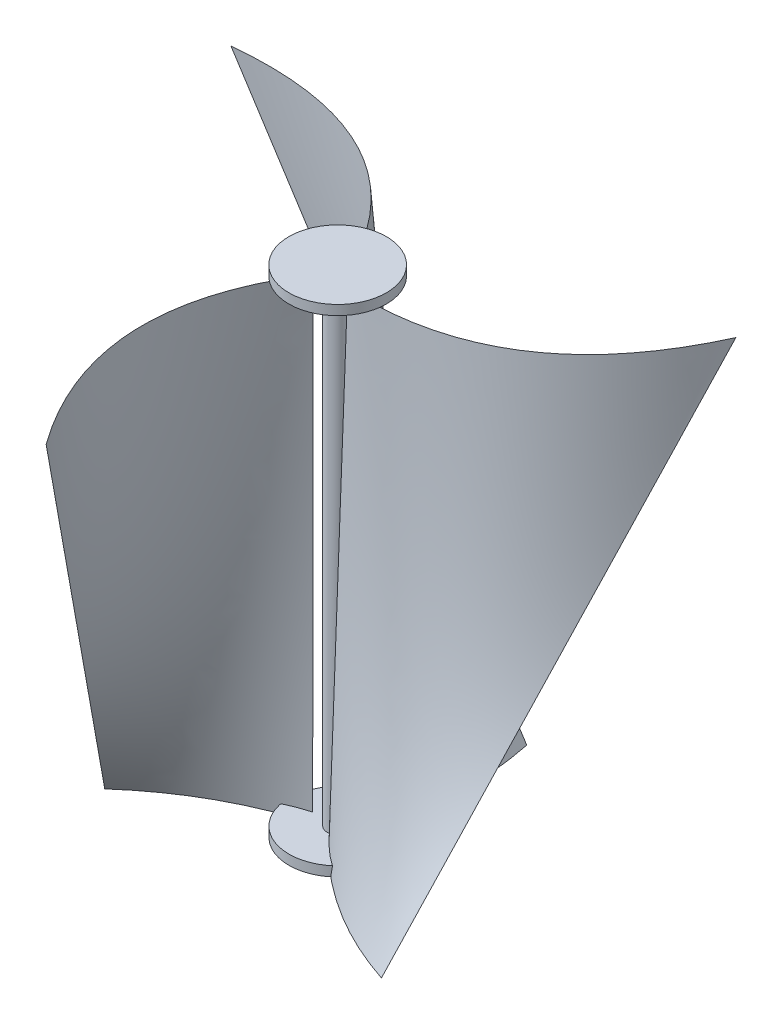
SolidWorks part; units mm, degrees
ref_plane "Front Plane" through (0, 0, 0) normal (0, 0, 1) x (1, 0, 0)
ref_plane "Top Plane" through (0, 0, 0) normal (0, 1, 0) x (1, 0, 0)
ref_plane "Right Plane" through (0, 0, 0) normal (1, 0, 0) x (0, 0, -1)
sketch "Sketch1" plane through (0, 0, 0) normal (0, 1, 0) x (1, 0, 0)
  circle A0 centre (0, 0) radius 50
  point P3 (0, 0)
extrude "Boss-Extrude1" add sketch "Sketch1" along normal blind 10 contours A0
ref_plane "Plane1" through (0, 500, 0) normal (0, 1, 0) x (1, 0, 0)
sketch "Sketch3" plane through (0, 0, 0) normal (0, 1, 0) x (1, 0, 0)
  spline S0 degree 2 poles (-162.8846, -76.5973) (-102.7497, -23.142) (-25.6862, 0) knots 0 0 0 1 1 1
sketch "Sketch5" plane through (0, 500, 0) normal (0, 1, 0) x (1, 0, 0)
  spline S0 degree 2 poles (0, -299.7964) (-105.1634, -153.4244) (-13.927, -11.2279) knots 0 0 0 1 1 1
surface "Surface-Loft2"
sketch "Sketch6" plane through (0, 0, 0) normal (0, 1, 0) x (1, 0, 0)
  line L0 (0, 0) -> (-96.5209, 96.5209)
pattern_circular "CirPattern1" count 3 over 360 about axis through (0, 10, 0) along (0, 1, 0) of bodies 103
sketch "Sketch7" plane through (0, 500, 0) normal (0, 1, 0) x (1, 0, 0)
  circle A0 centre (0, 0) radius 50.1082
extrude "Boss-Extrude2" add sketch "Sketch7" along normal blind 10 separate body
sketch "Sketch8" plane through (0, 0, 0) normal (0, 1, 0) x (1, 0, 0)
  circle A0 centre (0, 0) radius 10.8655
extrude "Boss-Extrude3" add sketch "Sketch8" along normal blind 500
